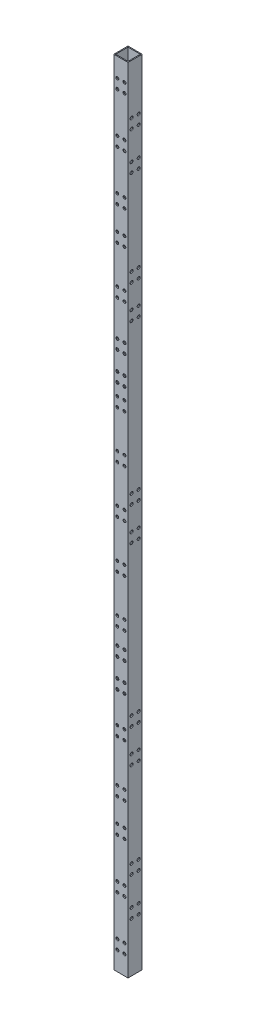
SolidWorks part; units mm, degrees
ref_plane "前视基准面" through (0, 0, 0) normal (0, 0, 1) x (1, 0, 0)
ref_plane "上视基准面" through (0, 0, 0) normal (0, 1, 0) x (1, 0, 0)
ref_plane "右视基准面" through (0, 0, 0) normal (1, 0, 0) x (0, 0, -1)
other "Configuration Table"
sketch "草图1" plane through (0, 0, 0) normal (0, 1, 0) x (1, 0, 0)
  line L1 (6.5, -6.5) -> (-6.5, -6.5)
  line L2 (6.5, -6.5) -> (6.5, 6.5)
  line L3 (6.5, 6.5) -> (-6.5, 6.5)
  line L4 (-6.5, -6.5) -> (-6.5, 6.5)
  line L5 (6.5, -6.5) -> (-6.5, 6.5) construction
  line L6 (6.5, 6.5) -> (-6.5, -6.5) construction
  line L7 (7.5, -7.5) -> (-7.5, -7.5)
  line L8 (7.5, -7.5) -> (7.5, 7.5)
  line L9 (7.5, 7.5) -> (-7.5, 7.5)
  line L10 (-7.5, -7.5) -> (-7.5, 7.5)
  line L11 (7.5, -7.5) -> (-7.5, 7.5) construction
  line L12 (7.5, 7.5) -> (-7.5, -7.5) construction
  point P0 (0, 0)
  point P6 (0, 0)
  dimension "D1" = 15
  dimension "D2" = 13
extrude "凸台-拉伸1" add sketch "草图1" along normal blind 835
sketch "草图2" plane through (0, 0, 7.5) normal (0, 0, 1) x (1, 0, 0)
  line L0 (0, 804.3358) -> (0, 762.8538) construction
  line L1 (-7.5, 757.5) -> (7.5, 757.5) construction
  line L2 (-7.5, 835) -> (-7.5, 0) construction
  line L3 (7.5, 835) -> (7.5, 0) construction
  line L4 (-7.5, 835) -> (7.5, 835) construction
  line L5 (-7.5, 417.5) -> (7.5, 417.5) construction
  line L6 (-7.5, 77.5) -> (7.5, 77.5) construction
  line L7 (-7.5, 810) -> (7.5, 810) construction
  line L8 (-7.5, 25) -> (7.5, 25) construction
  line L9 (-7.5, 687.5) -> (7.5, 687.5) construction
  line L10 (-7.5, 705) -> (7.5, 705) construction
  line L11 (-7.5, 670) -> (7.5, 670) construction
  line L12 (-7.5, 165) -> (7.5, 165) construction
  line L13 (-7.5, 130) -> (7.5, 130) construction
  line L14 (-7.5, 147.5) -> (7.5, 147.5) construction
  line L15 (7.5, 557.5) -> (-7.5, 557.5) construction
  line L16 (-7.5, 572.5) -> (7.5, 572.5) construction
  line L17 (-7.5, 542.5) -> (7.5, 542.5) construction
  line L18 (-7.5, 292.5) -> (7.5, 292.5) construction
  line L19 (-7.5, 262.5) -> (7.5, 262.5) construction
  line L20 (7.5, 277.5) -> (-7.5, 277.5) construction
  circle A0 centre (-3.75, 762.5) radius 1.575
  circle A1 centre (3.75, 762.5) radius 1.575
  circle A2 centre (-3.75, 752.5) radius 1.575
  circle A3 centre (3.75, 752.5) radius 1.575
  circle A4 centre (3.75, 82.5) radius 1.575
  circle A5 centre (-3.75, 82.5) radius 1.575
  circle A6 centre (3.75, 72.5) radius 1.575
  circle A7 centre (-3.75, 72.5) radius 1.575
  circle A8 centre (-3.75, 815) radius 1.6
  circle A10 centre (3.75, 815) radius 1.6
  circle A11 centre (3.75, 805) radius 1.6
  circle A12 centre (-3.75, 805) radius 1.6
  circle A13 centre (-3.75, 30) radius 1.6
  circle A14 centre (3.75, 30) radius 1.6
  circle A15 centre (3.75, 20) radius 1.6
  circle A16 centre (-3.75, 20) radius 1.6
  circle A17 centre (-3.75, 710) radius 1.51
  circle A18 centre (3.75, 710) radius 1.51
  circle A19 centre (3.75, 700) radius 1.51
  circle A20 centre (-3.75, 700) radius 1.51
  circle A21 centre (-3.75, 675) radius 1.51
  circle A22 centre (3.75, 675) radius 1.51
  circle A23 centre (3.75, 665) radius 1.51
  circle A24 centre (-3.75, 665) radius 1.51
  circle A25 centre (-3.75, 170) radius 1.51
  circle A26 centre (3.75, 170) radius 1.51
  circle A27 centre (3.75, 160) radius 1.51
  circle A28 centre (-3.75, 160) radius 1.51
  circle A29 centre (-3.75, 135) radius 1.51
  circle A30 centre (3.75, 135) radius 1.51
  circle A31 centre (3.75, 125) radius 1.51
  circle A32 centre (-3.75, 125) radius 1.51
  circle A33 centre (-3.75, 625) radius 1.51
  circle A34 centre (3.75, 615) radius 1.51
  circle A35 centre (3.75, 625) radius 1.51
  circle A36 centre (-3.75, 615) radius 1.51
  circle A41 centre (-3.75, 525) radius 1.51
  circle A42 centre (3.75, 515) radius 1.51
  circle A43 centre (3.75, 525) radius 1.51
  circle A44 centre (-3.75, 515) radius 1.51
  circle A45 centre (-3.75, 475) radius 1.51
  circle A46 centre (3.75, 465) radius 1.51
  circle A47 centre (3.75, 475) radius 1.51
  circle A48 centre (-3.75, 465) radius 1.51
  circle A49 centre (-3.75, 425) radius 1.51
  circle A50 centre (3.75, 415) radius 1.51
  circle A51 centre (3.75, 425) radius 1.51
  circle A52 centre (-3.75, 415) radius 1.51
  circle A53 centre (-3.75, 375) radius 1.51
  circle A54 centre (3.75, 365) radius 1.51
  circle A55 centre (3.75, 375) radius 1.51
  circle A56 centre (-3.75, 365) radius 1.51
  circle A57 centre (-3.75, 325) radius 1.51
  circle A58 centre (3.75, 315) radius 1.51
  circle A59 centre (3.75, 325) radius 1.51
  circle A60 centre (-3.75, 315) radius 1.51
  circle A65 centre (-3.75, 225) radius 1.51
  circle A66 centre (3.75, 215) radius 1.51
  circle A67 centre (3.75, 225) radius 1.51
  circle A68 centre (-3.75, 215) radius 1.51
  circle A69 centre (-3.75, 575) radius 1.51 [skipped]
  circle A70 centre (3.75, 565) radius 1.51 [skipped]
  circle A71 centre (3.75, 575) radius 1.51 [skipped]
  circle A72 centre (-3.75, 565) radius 1.51 [skipped]
  circle A73 centre (-3.75, 567.5) radius 1.6
  circle A74 centre (3.75, 567.5) radius 1.6
  circle A75 centre (3.75, 577.5) radius 1.6
  circle A76 centre (-3.75, 577.5) radius 1.6
  circle A77 centre (-3.75, 537.5) radius 1.6
  circle A78 centre (3.75, 537.5) radius 1.6
  circle A79 centre (3.75, 547.5) radius 1.6
  circle A80 centre (-3.75, 547.5) radius 1.6
  circle A81 centre (-3.75, 287.5) radius 1.6
  circle A82 centre (3.75, 287.5) radius 1.6
  circle A83 centre (3.75, 297.5) radius 1.6
  circle A84 centre (-3.75, 297.5) radius 1.6
  circle A85 centre (-3.75, 257.5) radius 1.6
  circle A86 centre (3.75, 257.5) radius 1.6
  circle A87 centre (3.75, 267.5) radius 1.6
  circle A88 centre (-3.75, 267.5) radius 1.6
  circle A89 centre (-3.75, 275) radius 1.51 [skipped]
  circle A90 centre (3.75, 275) radius 1.51 [skipped]
  circle A91 centre (3.75, 265) radius 1.51 [skipped]
  circle A92 centre (-3.75, 265) radius 1.51 [skipped]
  dimension "D2" = 3.15
  dimension "D5" = 25
  dimension "D8" = 5
  dimension "D6" = 3.2
  dimension "D11" = 3.02
  dimension "D18" = 3.2
  dimension "D1" = 77.5
  dimension "D3" = 7.5
  dimension "D4" = 10
  dimension "D9" = 147.5
  dimension "D7" = 3.75
  dimension "D10" = 17.5
  dimension "D12" = 3.75
  dimension "D13" = 5
  dimension "D15" = 50
  dimension "D16" = 277.5
  dimension "D17" = 15
  dimension "D19" = 3.75
  dimension "D20" = 5
  dimension "D14" = 10
extrude "切除-拉伸1" cut sketch "草图2" against normal up to surface (15 mm away) up to face at (0, 417.5, -7.5)
sketch "草图3" plane through (-7.5, 0, 0) normal (-1, 0, 0) x (0, 0, 1)
  line L0 (0, 809.7886) -> (0, 782.9032) construction
  line L1 (-7.5, 777.5) -> (7.5, 777.5) construction
  line L2 (-7.5, 835) -> (-7.5, 0) construction
  line L3 (7.5, 835) -> (7.5, 0) construction
  line L4 (-7.5, 835) -> (7.5, 835) construction
  line L5 (-7.5, 757.5) -> (7.5, 757.5) construction
  line L6 (7.5, 417.5) -> (-7.5, 417.5) construction
  line L7 (-7.5, 737.5) -> (7.5, 737.5) construction
  line L8 (-7.5, 97.5) -> (7.5, 97.5) construction
  line L9 (-7.5, 77.5) -> (7.5, 77.5) construction
  line L10 (-7.5, 57.5) -> (7.5, 57.5) construction
  line L11 (-7.5, 620) -> (7.5, 620) construction
  line L12 (-7.5, 637.5) -> (7.5, 637.5) construction
  line L13 (-7.5, 602.5) -> (7.5, 602.5) construction
  line L14 (-7.5, 232.5) -> (7.5, 232.5) construction
  line L15 (-7.5, 197.5) -> (7.5, 197.5) construction
  line L16 (-7.5, 215) -> (7.5, 215) construction
  line L17 (-7.5, 435) -> (7.5, 435) construction
  line L18 (-7.5, 400) -> (7.5, 400) construction
  circle A0 centre (-3.75, 782.5) radius 1.6
  circle A1 centre (3.75, 782.5) radius 1.6
  circle A2 centre (-3.75, 772.5) radius 1.6
  circle A3 centre (3.75, 772.5) radius 1.6
  circle A68 centre (3.75, 742.5) radius 1.6
  circle A69 centre (-3.75, 742.5) radius 1.6
  circle A70 centre (3.75, 732.5) radius 1.6
  circle A71 centre (-3.75, 732.5) radius 1.6
  circle A72 centre (-3.75, 102.5) radius 1.6
  circle A73 centre (3.75, 102.5) radius 1.6
  circle A74 centre (-3.75, 92.5) radius 1.6
  circle A75 centre (3.75, 92.5) radius 1.6
  circle A76 centre (3.75, 62.5) radius 1.6
  circle A77 centre (-3.75, 62.5) radius 1.6
  circle A78 centre (3.75, 52.5) radius 1.6
  circle A79 centre (-3.75, 52.5) radius 1.6
  circle A80 centre (-3.75, 642.5) radius 1.6
  circle A81 centre (3.75, 642.5) radius 1.6
  circle A82 centre (3.75, 632.5) radius 1.6
  circle A83 centre (-3.75, 632.5) radius 1.6
  circle A84 centre (-3.75, 607.5) radius 1.6
  circle A85 centre (3.75, 607.5) radius 1.6
  circle A86 centre (3.75, 597.5) radius 1.6
  circle A87 centre (-3.75, 597.5) radius 1.6
  circle A88 centre (-3.75, 237.5) radius 1.6
  circle A89 centre (3.75, 237.5) radius 1.6
  circle A90 centre (3.75, 227.5) radius 1.6
  circle A91 centre (-3.75, 227.5) radius 1.6
  circle A92 centre (-3.75, 202.5) radius 1.6
  circle A93 centre (3.75, 202.5) radius 1.6
  circle A94 centre (3.75, 192.5) radius 1.6
  circle A95 centre (-3.75, 192.5) radius 1.6
  circle A96 centre (-3.75, 440) radius 1.6
  circle A97 centre (3.75, 440) radius 1.6
  circle A98 centre (3.75, 430) radius 1.6
  circle A99 centre (-3.75, 430) radius 1.6
  circle A100 centre (-3.75, 405) radius 1.6
  circle A101 centre (3.75, 405) radius 1.6
  circle A102 centre (3.75, 395) radius 1.6
  circle A103 centre (-3.75, 395) radius 1.6
  dimension "D2" = 3.2
  dimension "D5" = 77.5
  dimension "D7" = 3.2
  dimension "D12" = 3.2
  dimension "D1" = 20
  dimension "D3" = 7.5
  dimension "D4" = 10
  dimension "D6" = 215
  dimension "D8" = 3.75
  dimension "D9" = 17.5
  dimension "D10" = 5
  dimension "D11" = 17.5
  dimension "D13" = 3.75
  dimension "D14" = 5
extrude "切除-拉伸2" cut sketch "草图3" against normal up to surface (15 mm away) up to face at (7.5, 417.5, 0)
